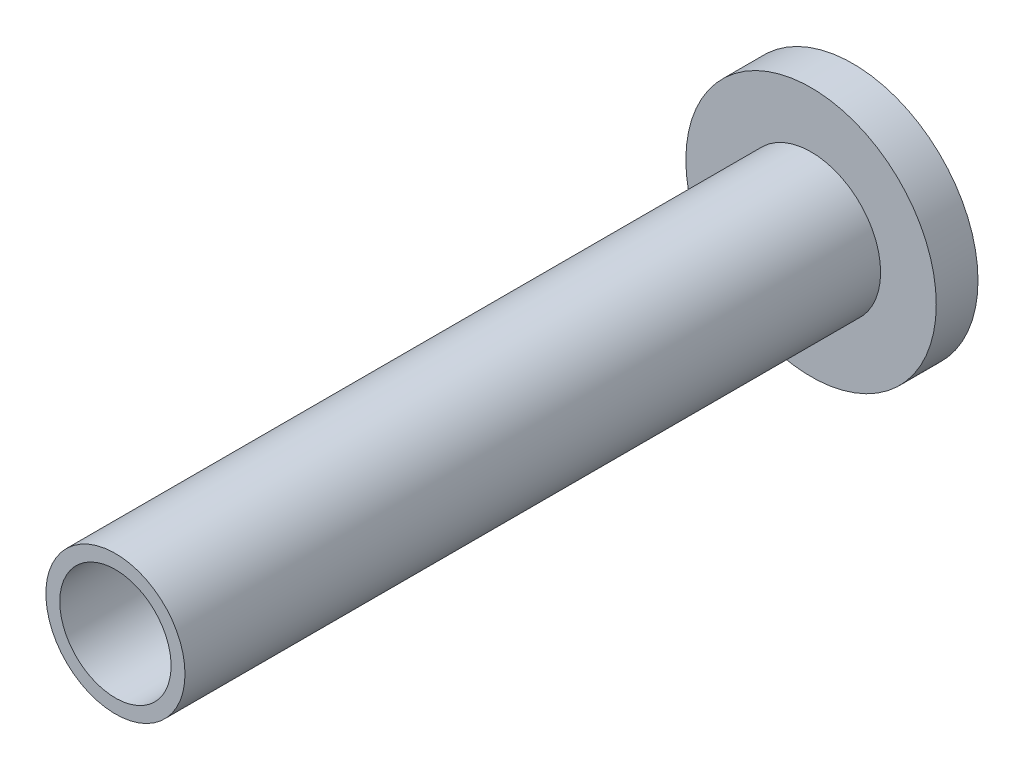
SolidWorks part; units mm, degrees
ref_plane "Plan de face" through (0, 0, 0) normal (0, 0, 1) x (1, 0, 0)
ref_plane "Plan de dessus" through (0, 0, 0) normal (0, 1, 0) x (1, 0, 0)
ref_plane "Plan de droite" through (0, 0, 0) normal (1, 0, 0) x (0, 0, -1)
sketch "Esquisse1" plane through (0, 0, 0) normal (0, 0, 1) x (1, 0, 0)
  circle A0 centre (0, 0) radius 2.5
  dimension "D1" = 5
extrude "Boss.-Extru.1" add sketch "Esquisse1" along normal blind 25
sketch "Esquisse2" plane through (0, 0, 0) normal (0, 0, 1) x (1, 0, 0)
  line L1 (-1.7187, 0.1158) -> (1.7187, 0.1158)
  line L2 (-1.7187, 0.1158) -> (-1.7187, -0.1158)
  line L3 (-1.7187, -0.1158) -> (1.7187, -0.1158)
  line L4 (1.7187, 0.1158) -> (1.7187, -0.1158)
  line L5 (-1.7187, 0.1158) -> (1.7187, -0.1158) construction
  line L6 (-1.7187, -0.1158) -> (1.7187, 0.1158) construction
  line L7 (-0.1158, -1.7187) -> (0.1158, -1.7187)
  line L8 (-0.1158, -1.7187) -> (-0.1158, 1.7187)
  line L9 (-0.1158, 1.7187) -> (0.1158, 1.7187)
  line L10 (0.1158, -1.7187) -> (0.1158, 1.7187)
  line L11 (-0.1158, -1.7187) -> (0.1158, 1.7187) construction
  line L12 (-0.1158, 1.7187) -> (0.1158, -1.7187) construction
  circle A0 centre (0, 0) radius 4.5
  dimension "D1" = 9
extrude "Boss.-Extru.2" add sketch "Esquisse2" against normal blind 1.5 contours A0 L10 L7 L8 L3 L2 L1 L9 L4
sketch "Esquisse3" plane through (0, 0, 25) normal (0, 0, 1) x (1, 0, 0)
  circle A0 centre (0, 0) radius 2
  dimension "D1" = 4
extrude "Enlèv. mat.-Extru.1" cut sketch "Esquisse3" against normal blind 10 and the other way through all
cosmetic thread "Représentation de filetage1" parameters "D2"=5
